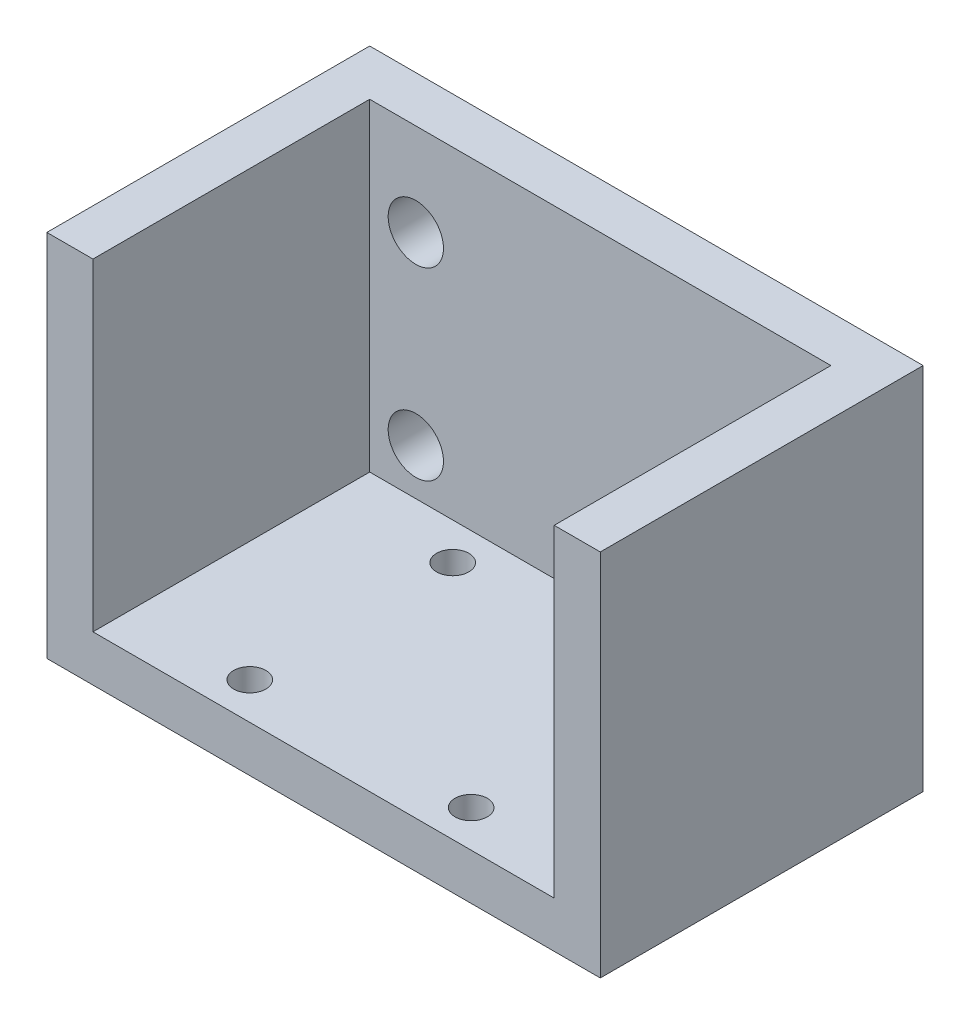
SolidWorks part; units mm, degrees
ref_plane "Спереди" through (0, 0, 0) normal (0, 0, 1) x (1, 0, 0)
ref_plane "Сверху" through (0, 0, 0) normal (0, 1, 0) x (1, 0, 0)
ref_plane "Справа" through (0, 0, 0) normal (1, 0, 0) x (0, 0, -1)
sketch "Эскиз1" plane through (0, 0, 0) normal (0, 1, 0) x (1, 0, 0)
  line L1 (0, 0) -> (60, 0)
  line L2 (0, 0) -> (0, 35)
  line L3 (0, 35) -> (60, 35)
  line L4 (60, 0) -> (60, 35)
  dimension "D1" = 35
  dimension "D2" = 60
extrude "Бобышка-Вытянуть1" add sketch "Эскиз1" along normal blind 5
sketch "Эскиз3" plane through (0, 5, 0) normal (0, 1, 0) x (1, 0, 0)
  line L0 (5, 30) -> (55, 30)
  line L1 (55, 30) -> (55, 0)
  line L2 (0, 0) -> (60, 0) construction
  line L3 (55, 0) -> (60, 0)
  line L4 (60, 0) -> (60, 35)
  line L5 (60, 35) -> (0, 35)
  line L6 (0, 35) -> (0, 0)
  line L7 (0, 0) -> (5, 0)
  line L8 (5, 0) -> (5, 30)
  dimension "D1" = 5
  dimension "D2" = 5
  dimension "D3" = 5
  dimension "D4" = 30
extrude "Бобышка-Вытянуть2" add sketch "Эскиз3" along normal blind 35
sketch "Эскиз4" plane through (0, 0, -35) normal (0, 0, -1) x (-1, 0, 0)
  line L0 (-30, 0) -> (-30, 40) construction
  line L1 (-60, 0) -> (0, 0) construction
  line L2 (-60, 40) -> (0, 40) construction
  line L3 (0, 10) -> (-60, 10) construction
  line L4 (0, 40) -> (0, 0) construction
  line L5 (-60, 40) -> (-60, 0) construction
  line L6 (-60, 30) -> (0, 30) construction
  line L7 (-60, 40) -> (-60, 0) construction
  circle A0 centre (-10, 10) radius 3
  circle A1 centre (-10, 30) radius 3
  circle A2 centre (-50, 30) radius 3
  circle A3 centre (-50, 10) radius 3
  dimension "D3" = 6
  dimension "D1" = 10
  dimension "D2" = 10
  dimension "D4" = 10
  dimension "D5" = 10
extrude "Вырез-Вытянуть1" cut sketch "Эскиз4" against normal up to surface (5 mm away) up to face at (30, 22.5, -30)
sketch "Эскиз5" plane through (0, 0, 0) normal (0, -1, 0) x (-1, 0, 0)
  line L0 (-30, 35) -> (-30, 0) construction
  line L1 (-60, 35) -> (0, 35) construction
  line L2 (0, 0) -> (-60, 0) construction
  line L3 (-42, 26) -> (-42, 4) construction
  line L4 (-42, 4) -> (-18, 4) construction
  line L5 (-18, 4) -> (-18, 26) construction
  line L6 (-18, 26) -> (-42, 26) construction
  circle A0 centre (-42, 26) radius 1.75
  circle A1 centre (-18, 26) radius 1.75
  circle A2 centre (-18, 4) radius 1.75
  circle A3 centre (-42, 4) radius 1.75
  point P8 (-30, 26)
  dimension "D3" = 3.5
  dimension "D1" = 22
  dimension "D2" = 24
  dimension "D4" = 9
extrude "Вырез-Вытянуть2" cut sketch "Эскиз5" against normal up to surface (5 mm away) up to face at (30, 5, -15)
